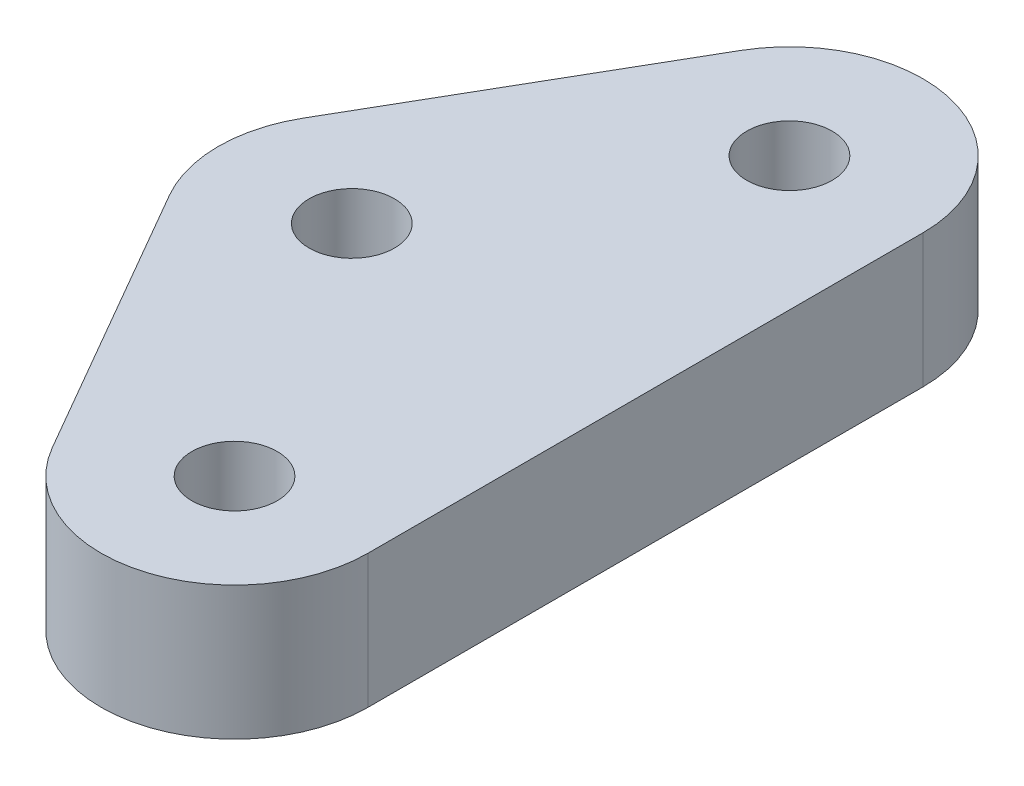
SolidWorks part; units mm, degrees
ref_plane "正面" through (0, 0, 0) normal (0, 0, 1) x (1, 0, 0)
ref_plane "平面" through (0, 0, 0) normal (0, 1, 0) x (1, 0, 0)
ref_plane "右側面" through (0, 0, 0) normal (1, 0, 0) x (0, 0, -1)
sketch "ｽｹｯﾁ1" plane through (0, 0, 0) normal (0, 1, 0) x (1, 0, 0)
  line L0 (11, 10.3923) -> (11, -10.3923)
  line L1 (-4.3301, -2.5) -> (1.6699, -12.8923)
  line L4 (-4.3301, 2.5) -> (1.6699, 12.8923)
  circle A0 centre (0, 0) radius 1.6
  circle A1 centre (6, 10.3923) radius 1.6
  circle A2 centre (6, -10.3923) radius 1.6
  arc A3 (11, 10.3923) -> (1.6699, 12.8923) centre (6, 10.3923) ccw
  arc A4 (1.6699, -12.8923) -> (11, -10.3923) centre (6, -10.3923) ccw
  arc A5 (-4.3301, 2.5) -> (-4.3301, -2.5) centre (0, 0) ccw
  dimension "D1" = 3.2
  dimension "D5" = 10
  dimension "D2" = 12
  dimension "D3" = 12
  dimension "D4" = 120
extrude "ﾎﾞｽ - 押し出し1" add sketch "ｽｹｯﾁ1" along normal blind 5
